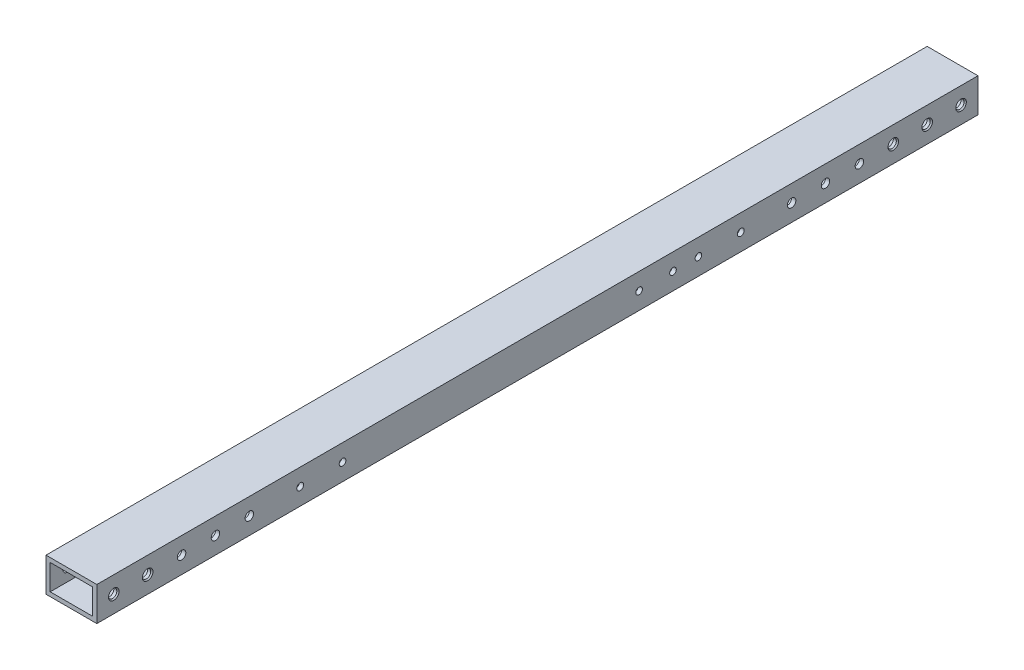
SolidWorks part; units mm, degrees
ref_plane "Front Plane" through (0, 0, 0) normal (0, 0, 1) x (1, 0, 0)
ref_plane "Top Plane" through (0, 0, 0) normal (0, 1, 0) x (1, 0, 0)
ref_plane "Right Plane" through (0, 0, 0) normal (1, 0, 0) x (0, 0, -1)
sketch "Sketch1" plane through (0, 0, 0) normal (0, 0, 1) x (1, 0, 0)
  line L0 (-15.875, 9.525) -> (15.875, 9.525)
  line L2 (-19.05, 12.7) -> (19.05, 12.7)
  line L3 (-19.05, 12.7) -> (-19.05, -12.7)
  line L4 (-19.05, -12.7) -> (19.05, -12.7)
  line L5 (19.05, 12.7) -> (19.05, -12.7)
  line L10 (15.875, 9.525) -> (15.875, -9.525)
  line L11 (-15.875, -9.525) -> (15.875, -9.525)
  line L12 (-15.875, 9.525) -> (-15.875, -9.525)
  point P12 (0, 12.7)
  point P14 (19.05, 0)
  dimension "Wall Thickness" = 3.175
  dimension "Outside Width" = 38.1
  dimension "Outside Height" = 25.4
  dimension "Inside Height" = 19.05
  dimension "Inside Width" = 31.75
sketch "Sketch2" plane through (0, 0, 0) normal (1, 0, 0) x (0, 0, -1)
  line L0 (330.2, 0) -> (-330.2, 0)
  point P4 (0, 0)
  point P7 (-330.2, 0)
  point P10 (330.2, 0)
  dimension "Length" = 660.4
sketch "Sketch3" plane through (0, 0, 0) normal (0, 0, 1) x (1, 0, 0)
  line L21 (19.05, 12.7) -> (-19.05, 12.7)
  line L22 (19.05, -12.7) -> (19.05, 12.7)
  line L23 (-19.05, -12.7) -> (19.05, -12.7)
  line L24 (-19.05, 12.7) -> (-19.05, -12.7)
  line L25 (19.05, 12.7) -> (-19.05, 12.7)
  line L26 (19.05, -12.7) -> (19.05, 12.7)
  line L27 (-19.05, -12.7) -> (19.05, -12.7)
  line L28 (-19.05, 12.7) -> (-19.05, -12.7)
  line L29 (15.875, 9.525) -> (-15.875, 9.525)
  line L30 (15.875, -9.525) -> (15.875, 9.525)
  line L31 (-15.875, -9.525) -> (15.875, -9.525)
  line L32 (-15.875, 9.525) -> (-15.875, -9.525)
  line L33 (15.875, 9.525) -> (-15.875, 9.525)
  line L34 (15.875, -9.525) -> (15.875, 9.525)
  line L35 (-15.875, -9.525) -> (15.875, -9.525)
  line L36 (-15.875, 9.525) -> (-15.875, -9.525)
  dimension "D1" = 0
  dimension "D2" = 0
extrude "Boss-Extrude1" add sketch "Sketch3" along normal up to vertex (330.2 mm away) and the other way up to vertex (330.2 mm away) up to point (0, 0, 330.2) other way up to point (0, 0, -330.2)
sketch "Drawing Reference" plane through (0, 0, 0) normal (1, 0, 0) x (0, 0, -1)
  line L0 (-330.2, 0) -> (330.2, 0) construction
  line L1 (0, -12.7) -> (0, 12.7) construction
  line L2 (-330.2, -12.7) -> (330.2, -12.7) construction
  line L5 (-330.2, 12.7) -> (330.2, 12.7) construction
  point P7 (-302.768, 0)
  point P8 (302.768, 0)
  dimension "D1" = 27.432
sketch "Sketch4" plane through (-19.05, 0, 0) normal (-1, 0, 0) x (0, 0, 1)
  line L0 (-330.2, 0) -> (-317.5, 0)
  line L1 (-330.2, 12.7) -> (-330.2, -12.7) construction
  line L2 (-317.5, 0) -> (-292.1, 0)
  line L3 (-292.1, 0) -> (-266.7, 0)
  line L4 (-266.7, 0) -> (-241.3, 0)
  line L5 (-241.3, 0) -> (-215.9, 0)
  line L6 (-215.9, 0) -> (-190.5, 0)
  line L7 (330.2, 0) -> (317.5, 0)
  line L8 (330.2, 12.7) -> (330.2, -12.7) construction
  line L9 (317.5, 0) -> (292.1, 0)
  line L10 (292.1, 0) -> (266.7, 0)
  line L11 (266.7, 0) -> (241.3, 0)
  line L12 (241.3, 0) -> (215.9, 0)
  line L13 (-190.5, 0) -> (-120.65, 0)
  line L14 (-190.5, 0) -> (-152.4, 0) construction
  line L15 (215.9, 0) -> (146.05, 0)
hole_wizard "1/4 (0.25) Diameter Hole2" positions "Sketch7" profile "Sketch8" hole size "1/4" standard "ANSI Inch" end condition through all
sketch "Sketch7" plane through (-19.05, 0, 0) normal (-1, 0, 0) x (0, 0, 1)
  point P0 (-317.5, 0)
  point P3 (-292.1, 0)
  point P7 (317.5, 0)
  point P11 (-266.7, 0)
  point P14 (292.1, 0)
sketch "Sketch8" plane through (-19.05, 0, -317.5) normal (0, 1, 0) x (0, 0, 1)
  line L0 (0, 0) -> (0, 38.1)
  line L1 (0, 38.1) -> (3.9624, 38.1)
  line L2 (3.175, 37.1942) -> (3.175, 0)
  line L5 (3.175, 0) -> (0, 0)
  line L7 (3.9624, 38.1) -> (3.175, 37.1942)
  line L8 (-3.9624, 38.1) -> (-3.175, 37.1942) construction
  line L11 (0, -6.35) -> (0, 107.95) construction
  dimension "Thru Hole Dia." = 6.35
  dimension "Thru Hole Depth" = 38.1
  dimension "Far C'Sink Dia." = 7.9248
  dimension "Far C'Sink Angle" = 82
hole_wizard "1/4 (0.25) Diameter Hole3" positions "Sketch9" profile "Sketch10" hole size "1/4" standard "ANSI Inch" end condition through all
sketch "Sketch9" plane through (19.05, 0, 0) normal (1, 0, 0) x (0, 0, -1)
  point P0 (-266.7, 0)
  point P3 (-241.3, 0)
  point P6 (-215.9, 0)
  point P9 (241.3, 0)
  point P12 (215.9, 0)
  point P15 (190.5, 0)
sketch "Sketch10" plane through (19.05, 0, 266.7) normal (0, 1, 0) x (0, 0, -1)
  line L0 (0, 0) -> (0, 38.1)
  line L1 (0, 38.1) -> (3.175, 38.1)
  line L2 (3.175, 38.1) -> (3.175, 0)
  line L5 (3.175, 0) -> (0, 0)
  line L11 (0, -6.35) -> (0, 107.95) construction
  dimension "Thru Hole Dia." = 6.35
  dimension "Thru Hole Depth" = 38.1
hole_wizard "13/64 (0.20313) Diameter Hole1" positions "Sketch11" profile "Sketch12" hole size "13/64" standard "ANSI Inch" end condition through all
sketch "Sketch11" plane through (19.05, 0, 0) normal (1, 0, 0) x (0, 0, -1)
  point P0 (152.4, 0)
  point P7 (-177.8, 0)
sketch "Sketch12" plane through (19.05, 0, -152.4) normal (0, 1, 0) x (0, 0, -1)
  line L0 (0, 0) -> (0, 38.1)
  line L1 (0, 38.1) -> (2.5798, 38.1)
  line L2 (2.5798, 38.1) -> (2.5798, 0)
  line L5 (2.5798, 0) -> (0, 0)
  line L11 (0, -6.35) -> (0, 107.95) construction
  dimension "Thru Hole Dia." = 5.1595
  dimension "Thru Hole Depth" = 38.1
hole_wizard "#10 Clearance Hole1" positions "Sketch13" profile "Sketch14" hole size "#10" standard "ANSI Inch" end condition through all
sketch "Sketch13" plane through (-19.05, 0, 0) normal (-1, 0, 0) x (0, 0, 1)
  point P0 (-120.65, 0)
  point P3 (146.05, 0)
  point P7 (-101.6, 0)
  point P9 (-76.2, 0)
sketch "Sketch14" plane through (-19.05, 0, -120.65) normal (0, 1, 0) x (0, 0, 1)
  line L0 (0, 0) -> (0, 38.1)
  line L1 (0, 38.1) -> (2.4892, 38.1)
  line L2 (2.4892, 38.1) -> (2.4892, 0)
  line L5 (2.4892, 0) -> (0, 0)
  line L11 (0, -6.35) -> (0, 107.95) construction
  dimension "Thru Hole Dia." = 4.9784
  dimension "Thru Hole Depth" = 38.1
equation "\"D1@Drawing Reference\"=\"Outside Width@Sketch1\" * 0.72"
